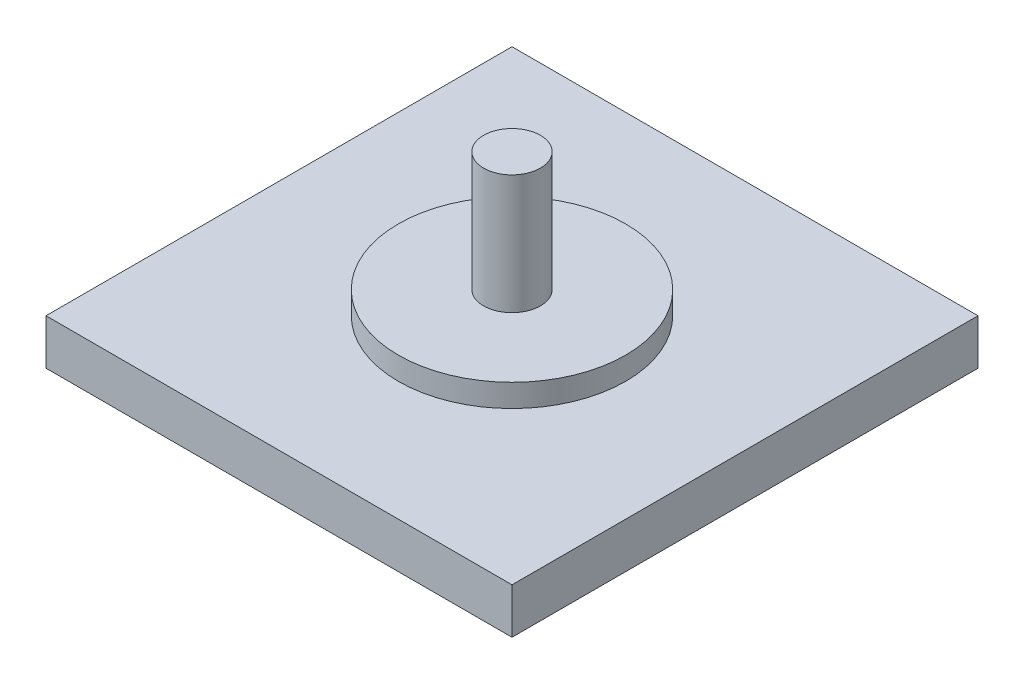
SolidWorks part; units mm, degrees
ref_plane "前视基准面" through (0, 0, 0) normal (0, 0, 1) x (1, 0, 0)
ref_plane "上视基准面" through (0, 0, 0) normal (0, 1, 0) x (1, 0, 0)
ref_plane "右视基准面" through (0, 0, 0) normal (1, 0, 0) x (0, 0, -1)
sketch "草图1" plane through (0, 0, 0) normal (0, 1, 0) x (1, 0, 0)
  line L1 (-20.5, -20.5) -> (20.5, -20.5)
  line L2 (-20.5, -20.5) -> (-20.5, 20.5)
  line L3 (-20.5, 20.5) -> (20.5, 20.5)
  line L4 (20.5, -20.5) -> (20.5, 20.5)
  line L5 (-20.5, -20.5) -> (20.5, 20.5) construction
  line L6 (-20.5, 20.5) -> (20.5, -20.5) construction
  point P0 (0, 0)
  dimension "D1" = 41
  dimension "D2" = 41
extrude "凸台-拉伸1" add sketch "草图1" along normal blind 4
sketch "草图2" plane through (0, 4, 0) normal (0, 1, 0) x (1, 0, 0)
  circle A0 centre (0, 0) radius 10
  dimension "D1" = 20
extrude "凸台-拉伸2" add sketch "草图2" along normal blind 2
sketch "草图3" plane through (0, 6, 0) normal (0, 1, 0) x (1, 0, 0)
  circle A0 centre (0, 0) radius 2.5
  dimension "D1" = 5
extrude "凸台-拉伸3" add sketch "草图3" along normal blind 10.5
